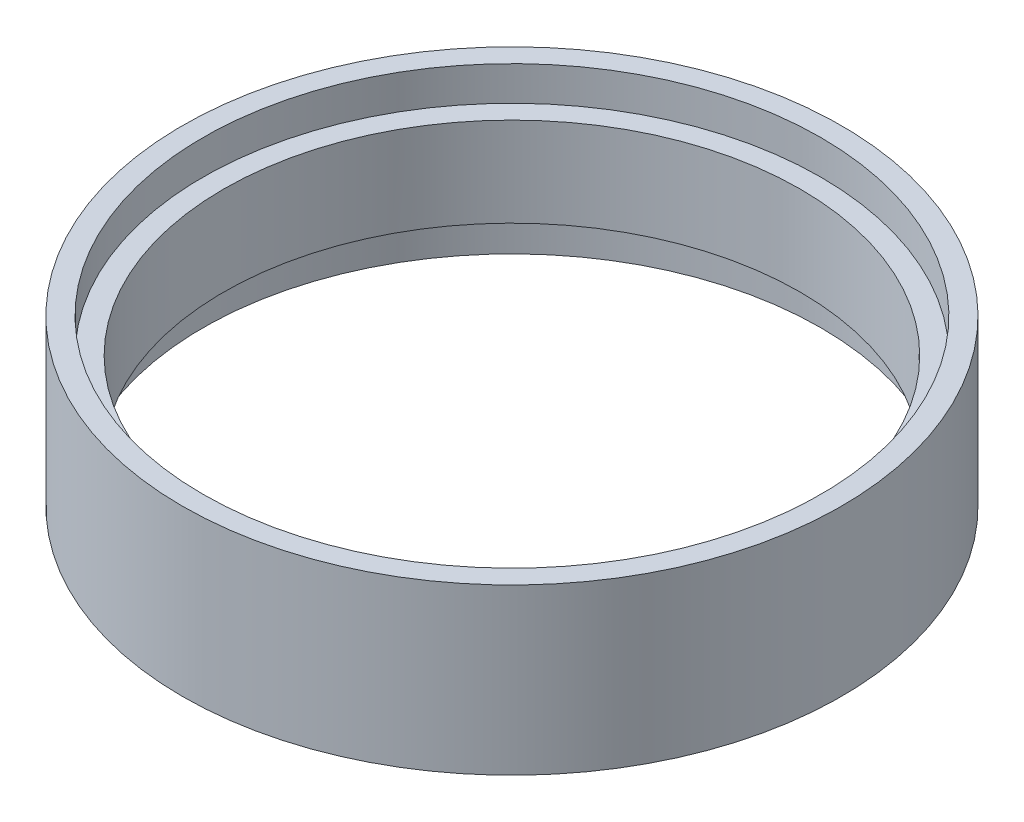
SolidWorks part; units mm, degrees
ref_plane "Ebene vorne" through (0, 0, 0) normal (0, 0, 1) x (1, 0, 0)
ref_plane "Ebene oben" through (0, 0, 0) normal (0, 1, 0) x (1, 0, 0)
ref_plane "Ebene rechts" through (0, 0, 0) normal (1, 0, 0) x (0, 0, -1)
sketch "Skizze1" plane through (0, 0, 0) normal (0, 1, 0) x (1, 0, 0)
  circle A0 centre (0, 0) radius 48
  circle A1 centre (0, 0) radius 42
extrude "Aufsatz-Linear austragen2" add sketch "Skizze1" along normal blind 24 contours A1 | A0
sketch "Skizze2" plane through (0, 24, 0) normal (0, 1, 0) x (1, 0, 0)
  circle A0 centre (0, 0) radius 45
extrude "Schnitt-Linear austragen1" cut sketch "Skizze2" against normal blind 5 contours A0
sketch "Skizze4" plane through (0, 0, 0) normal (0, -1, 0) x (1, 0, 0)
  circle A0 centre (0, 0) radius 45
extrude "Schnitt-Linear austragen2" cut sketch "Skizze4" against normal blind 6
